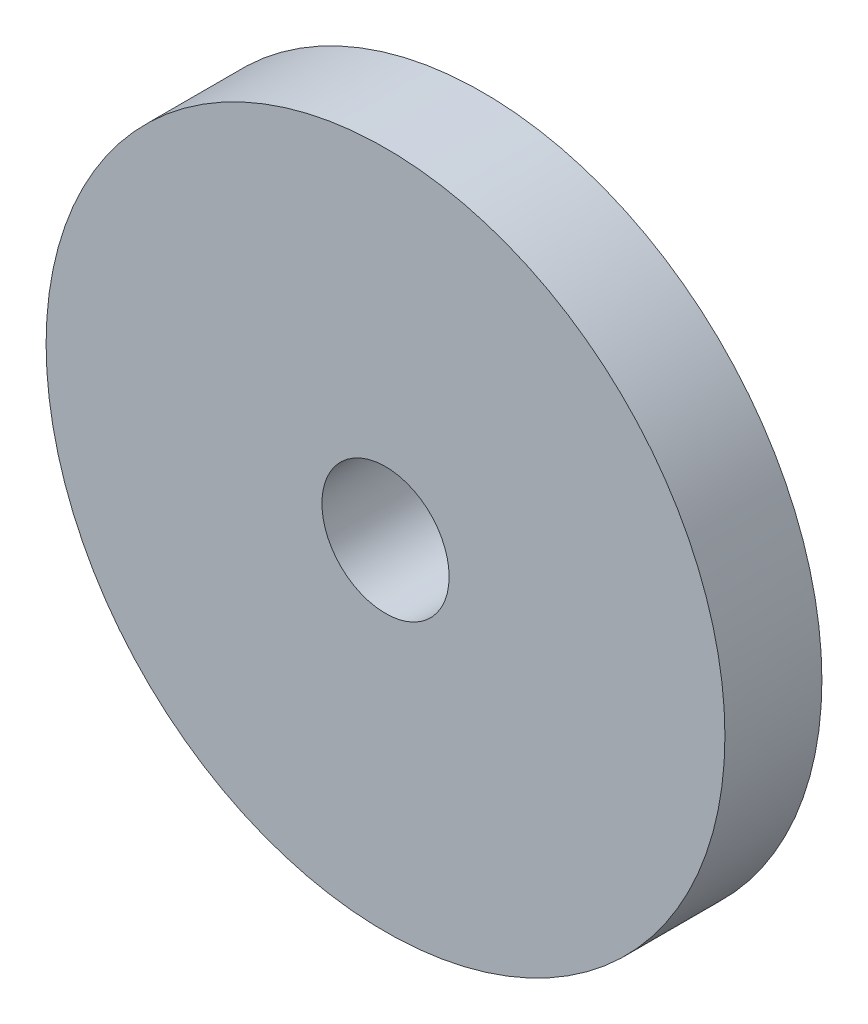
SolidWorks part; units mm, degrees
material "Alloy Steel"
ref_plane "Front Plane" through (0, 0, 0) normal (0, 0, 1) x (1, 0, 0)
ref_plane "Top Plane" through (0, 0, 0) normal (0, 1, 0) x (1, 0, 0)
ref_plane "Right Plane" through (0, 0, 0) normal (1, 0, 0) x (0, 0, -1)
sketch "Sketch1" plane through (0, 0, 0) normal (0, 0, 1) x (1, 0, 0)
  circle A0 centre (0, 0) radius 11.1125
  dimension "D1" = 22.225
extrude "Boss-Extrude1" add sketch "Sketch1" along normal blind 3.175
sketch "Sketch2" plane through (0, 0, 3.175) normal (0, 0, 1) x (1, 0, 0)
  circle A0 centre (0, 0) radius 2.0828
  dimension "D1" = 4.1656
extrude "Cut-Extrude1" cut sketch "Sketch2" against normal through all
